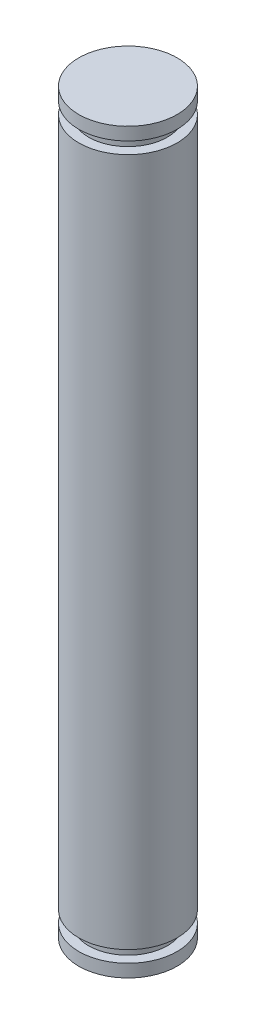
SolidWorks part; units mm, degrees
ref_plane "前视基准面" through (0, 0, 0) normal (0, 0, 1) x (1, 0, 0)
ref_plane "上视基准面" through (0, 0, 0) normal (0, 1, 0) x (1, 0, 0)
ref_plane "右视基准面" through (0, 0, 0) normal (1, 0, 0) x (0, 0, -1)
sketch "草图1" plane through (0, 0, 0) normal (0, 0, 1) x (1, 0, 0)
  line L0 (0, 0) -> (-5, 0)
  line L2 (-5, 75) -> (0, 75)
  line L3 (0, 75) -> (0, 0) construction
  line L4 (-5, 0) -> (-5, 1.3)
  line L5 (-5, 1.3) -> (-4, 1.3)
  line L6 (-4, 1.3) -> (-4, 2.5)
  line L7 (-4, 2.5) -> (-5, 2.5)
  line L8 (-5, 2.5) -> (-5, 72.5)
  line L9 (-5, 72.5) -> (-4, 72.5)
  line L10 (-4, 72.5) -> (-4, 73.7)
  line L11 (-4, 73.7) -> (-5, 73.7)
  line L12 (-5, 73.7) -> (-5, 75)
  line L13 (0, 0) -> (0, 75)
  dimension "D1" = 75
  dimension "D2" = 70
  dimension "D3" = 1.2
  dimension "D4" = 1
  dimension "D5" = 5
revolve "旋转1" add sketch "草图1" angle 360 about L3
